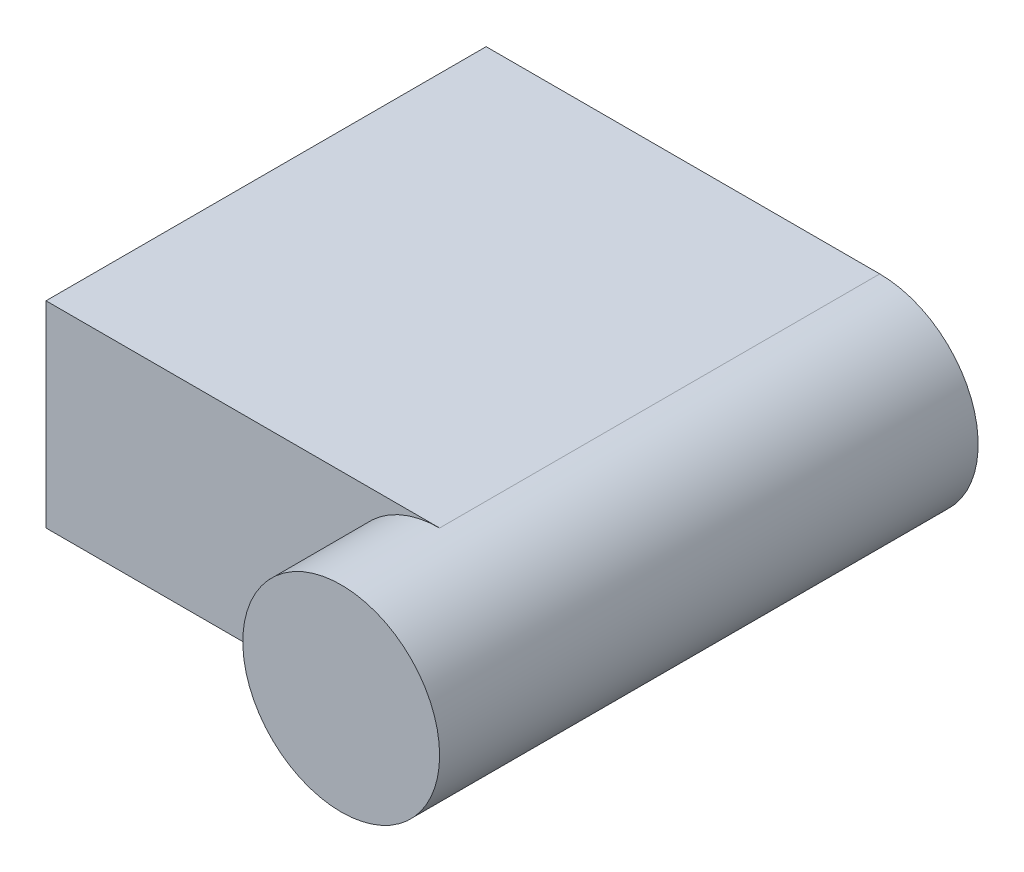
SolidWorks part; units mm, degrees
ref_plane "前视基准面" through (0, 0, 0) normal (0, 0, 1) x (1, 0, 0)
ref_plane "上视基准面" through (0, 0, 0) normal (0, 1, 0) x (1, 0, 0)
ref_plane "右视基准面" through (0, 0, 0) normal (1, 0, 0) x (0, 0, -1)
other "Configuration Table"
sketch "草图1" plane through (0, 0, 0) normal (0, 0, 1) x (1, 0, 0)
  line L0 (0, 0) -> (100, 0)
  line L1 (100, 0) -> (100, 20)
  line L2 (100, 20) -> (0, 20)
  line L3 (0, 20) -> (0, 0)
  dimension "D1" = 20
  dimension "D2" = 100
extrude "凸台-拉伸1" add sketch "草图1" along normal blind 44.73
sketch "草图3" plane through (0, 0, 44.73) normal (0, 0, 1) x (1, 0, 0)
  line L4 (0, 20) -> (0, 0)
  line L5 (0, 0) -> (100, 0)
  line L6 (100, 0) -> (100, 20)
  line L7 (100, 20) -> (0, 20)
  line L8 (0, 20) -> (0, 0)
  line L9 (0, 0) -> (100, 0)
  line L10 (100, 0) -> (100, 20)
  line L11 (100, 20) -> (0, 20)
  circle A0 centre (40, 10) radius 10
  dimension "D2" = 20
  dimension "D3" = 40
  dimension "D1" = 0
extrude "凸台-拉伸2" add sketch "草图3" along normal blind 10 contours A0 L9
sketch "草图4" plane through (0, 0, 44.73) normal (0, 0, 1) x (1, 0, 0)
  line L3 (40, 0) -> (100, 0)
  line L4 (100, 0) -> (100, 20)
  line L5 (100, 20) -> (40, 20)
  line L6 (40, 0) -> (100, 0)
  line L7 (100, 0) -> (100, 20)
  line L8 (100, 20) -> (40, 20)
  arc A1 (40, 0) -> (40, 20) centre (40, 10) ccw
  arc A2 (40, 0) -> (40, 20) centre (40, 10) ccw
  dimension "D1" = 0
extrude "切除-拉伸1" cut sketch "草图4" against normal up to surface (44.73 mm away) up to face at (50, 10, 0)
